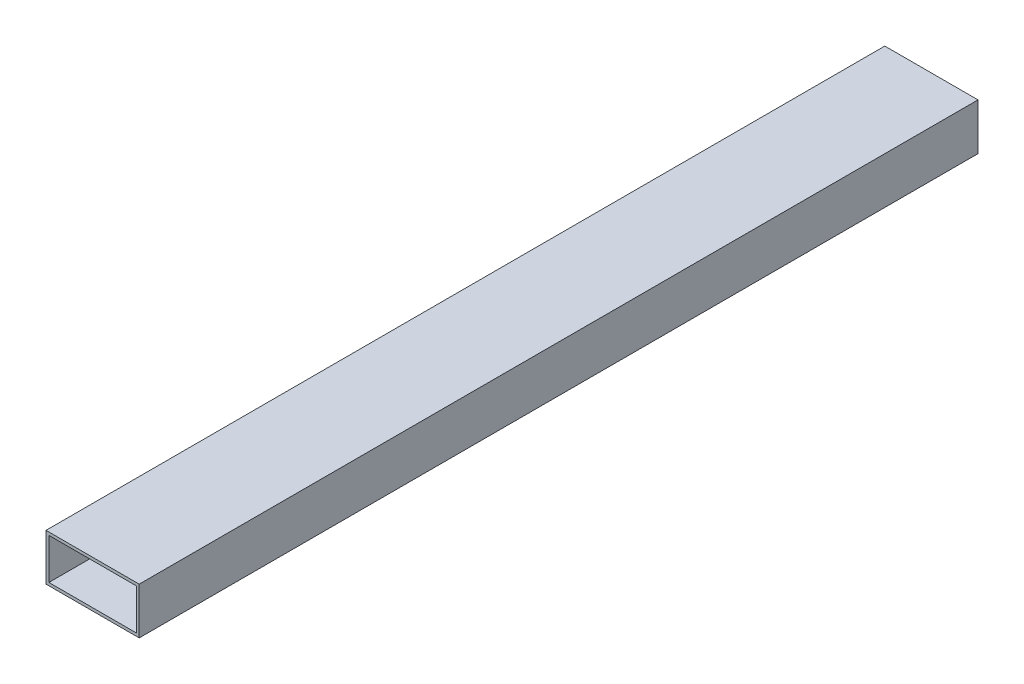
SolidWorks part; units mm, degrees
ref_plane "Front Plane" through (0, 0, 0) normal (0, 0, 1) x (1, 0, 0)
ref_plane "Top Plane" through (0, 0, 0) normal (0, 1, 0) x (1, 0, 0)
ref_plane "Right Plane" through (0, 0, 0) normal (1, 0, 0) x (0, 0, -1)
sketch "Sketch1" plane through (0, 0, 0) normal (0, 0, 1) x (1, 0, 0)
  line L0 (-23.8125, 11.1125) -> (23.8125, 11.1125)
  line L2 (-25.4, 12.7) -> (25.4, 12.7)
  line L3 (-25.4, 12.7) -> (-25.4, -12.7)
  line L4 (-25.4, -12.7) -> (25.4, -12.7)
  line L5 (25.4, 12.7) -> (25.4, -12.7)
  line L10 (23.8125, 11.1125) -> (23.8125, -11.1125)
  line L11 (-23.8125, -11.1125) -> (23.8125, -11.1125)
  line L12 (-23.8125, 11.1125) -> (-23.8125, -11.1125)
  point P12 (0, 12.7)
  point P14 (25.4, 0)
  dimension "Wall Thickness" = 1.5875
  dimension "Outside Width" = 50.8
  dimension "Outside Height" = 25.4
  dimension "Inside Height" = 22.225
  dimension "Inside Width" = 47.625
sketch "Sketch2" plane through (0, 0, 0) normal (1, 0, 0) x (0, 0, -1)
  line L0 (228.6, 0) -> (-228.6, 0)
  point P4 (0, 0)
  point P7 (-228.6, 0)
  point P10 (228.6, 0)
  dimension "Length" = 457.2
sketch "Sketch3" plane through (0, 0, 0) normal (0, 0, 1) x (1, 0, 0)
  line L21 (25.4, 12.7) -> (-25.4, 12.7)
  line L22 (25.4, -12.7) -> (25.4, 12.7)
  line L23 (-25.4, -12.7) -> (25.4, -12.7)
  line L24 (-25.4, 12.7) -> (-25.4, -12.7)
  line L25 (25.4, 12.7) -> (-25.4, 12.7)
  line L26 (25.4, -12.7) -> (25.4, 12.7)
  line L27 (-25.4, -12.7) -> (25.4, -12.7)
  line L28 (-25.4, 12.7) -> (-25.4, -12.7)
  line L29 (23.8125, 11.1125) -> (-23.8125, 11.1125)
  line L30 (23.8125, -11.1125) -> (23.8125, 11.1125)
  line L31 (-23.8125, -11.1125) -> (23.8125, -11.1125)
  line L32 (-23.8125, 11.1125) -> (-23.8125, -11.1125)
  line L33 (23.8125, 11.1125) -> (-23.8125, 11.1125)
  line L34 (23.8125, -11.1125) -> (23.8125, 11.1125)
  line L35 (-23.8125, -11.1125) -> (23.8125, -11.1125)
  line L36 (-23.8125, 11.1125) -> (-23.8125, -11.1125)
  dimension "D1" = 0
  dimension "D2" = 0
extrude "Boss-Extrude1" add sketch "Sketch3" along normal up to vertex (228.6 mm away) and the other way up to vertex (228.6 mm away) up to point (0, 0, 228.6) other way up to point (0, 0, -228.6)
sketch "Drawing Reference" plane through (0, 0, 0) normal (1, 0, 0) x (0, 0, -1)
  line L0 (-228.6, 0) -> (228.6, 0) construction
  line L1 (0, -12.7) -> (0, 12.7) construction
  line L2 (-228.6, -12.7) -> (228.6, -12.7) construction
  line L5 (-228.6, 12.7) -> (228.6, 12.7) construction
  point P7 (-192.024, 0)
  point P8 (192.024, 0)
  dimension "D1" = 36.576
equation "\"D1@Drawing Reference\"=\"Outside Width@Sketch1\" * 0.72"
